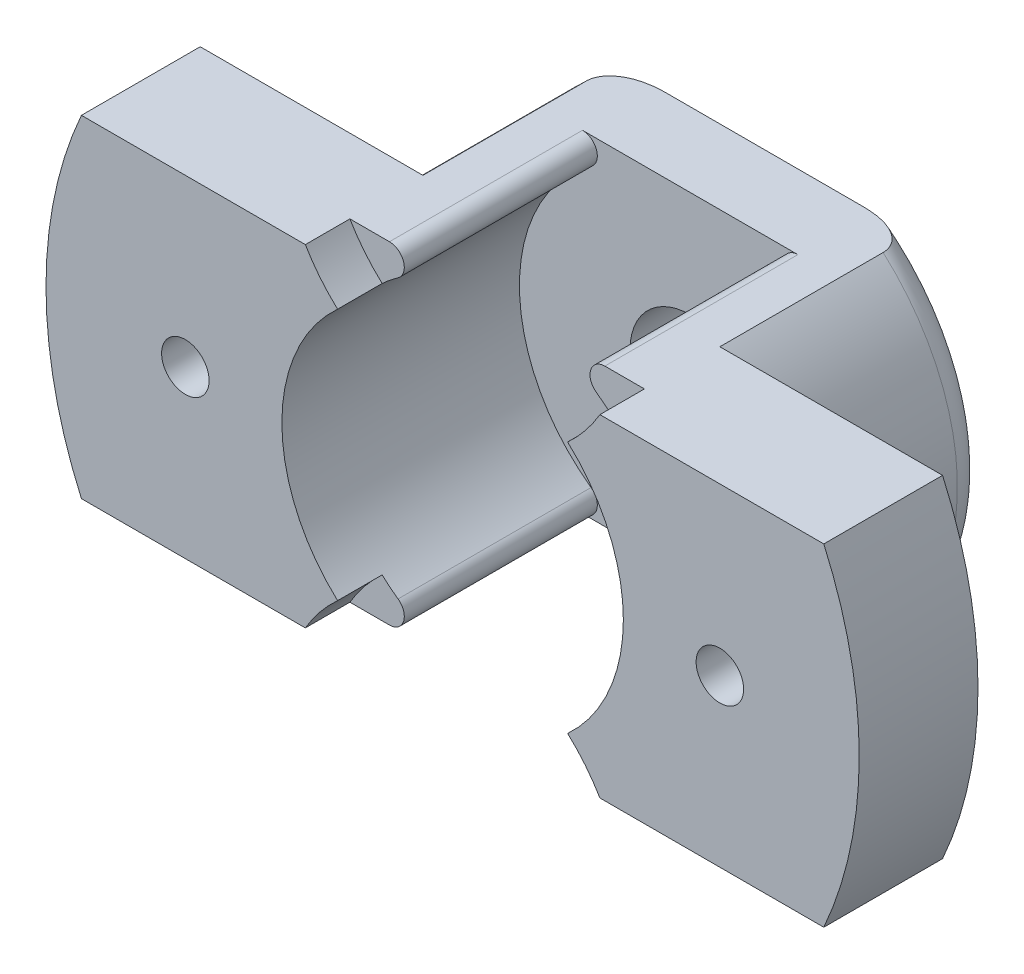
SolidWorks part; units mm, degrees
ref_plane "前视基准面" through (0, 0, 0) normal (0, 0, 1) x (1, 0, 0)
ref_plane "上视基准面" through (0, 0, 0) normal (0, 1, 0) x (1, 0, 0)
ref_plane "右视基准面" through (0, 0, 0) normal (1, 0, 0) x (0, 0, -1)
sketch "草图1" plane through (0, 0, 0) normal (0, 0, 1) x (1, 0, 0)
  line L0 (-10, 11.1803) -> (10, 11.1803)
  line L1 (-10, -11.1803) -> (10, -11.1803)
  line L2 (-10, 11.1803) -> (-10, -11.1803)
  line L3 (10, 11.1803) -> (10, -11.1803)
  circle A0 centre (0, 0) radius 15
  dimension "D1" = 30
  dimension "D2" = 20
extrude "凸台-拉伸1" add sketch "草图1" along normal blind 5 contours L2 A0 | L3 L0 L2 L1 | L3 A0
sketch "草图2" plane through (0, 0, 0) normal (0, 0, -1) x (-1, 0, 0)
  circle A0 centre (0, 0) radius 4.05
  dimension "D1" = 8.1
extrude "切除-拉伸1" cut sketch "草图2" against normal blind 5
sketch "草图3" plane through (0, 0, 5) normal (0, 0, 1) x (1, 0, 0)
  line L0 (-10, 11.1803) -> (10, 11.1803) construction
  line L1 (-10, 11.1803) -> (-2.6926, 11.1803)
  line L2 (-10, -11.1803) -> (10, -11.1803) construction
  line L3 (-10, -11.1803) -> (-2.6926, -11.1803)
  line L4 (2.6926, 11.1803) -> (10, 11.1803)
  line L5 (2.6926, -11.1803) -> (10, -11.1803)
  arc A1 (10, -11.1803) -> (10, 11.1803) centre (0, 0) ccw construction
  arc A2 (10, -11.1803) -> (10, 11.1803) centre (0, 0) ccw
  arc A3 (-10, 11.1803) -> (-10, -11.1803) centre (0, 0) ccw construction
  arc A4 (-10, 11.1803) -> (-10, -11.1803) centre (0, 0) ccw
  arc A6 (-2.6926, 11.1803) -> (-2.6926, -11.1803) centre (0, 0) ccw
  arc A7 (2.6926, -11.1803) -> (2.6926, 11.1803) centre (0, 0) ccw
  dimension "D1" = 23
extrude "凸台-拉伸2" add sketch "草图3" along normal blind 16
sketch "草图4" plane through (0, 0, 21) normal (0, 0, 1) x (1, 0, 0)
  line L0 (10, 11.1803) -> (2.6926, 11.1803) construction
  line L1 (10, -11.1803) -> (25, -11.1803)
  line L2 (2.6926, -11.1803) -> (10, -11.1803) construction
  line L3 (10, 11.1803) -> (25, 11.1803)
  line L4 (0, 0) -> (0, 11.1803) construction
  line L5 (-2.6926, 11.1803) -> (2.6926, 11.1803) construction
  arc A0 (-10, 11.1803) -> (-10, -11.1803) centre (0, 0) ccw construction
  arc A1 (10, -11.1803) -> (10, 11.1803) centre (0, 0) ccw construction
  arc A2 (-10, 11.1803) -> (-10, -11.1803) centre (0, 0) ccw
  arc A3 (10, -11.1803) -> (10, 11.1803) centre (0, 0) ccw
  arc A4 (25, -11.1803) -> (25, 11.1803) centre (0, 0) ccw
  dimension "D2" = 15
extrude "凸台-拉伸3" add sketch "草图4" against normal blind 8 contours L1 A4 L3 A3
mirror "镜向1" about plane through (0, 0, 0) normal (1, 0, 0) of "凸台-拉伸3"
sketch "草图5" plane through (0, 0, 21) normal (0, 0, 1) x (1, 0, 0)
  line L0 (0, -7.4334) -> (0, 8.8357) construction
  circle A0 centre (0, 17) radius 11.5
  circle A1 centre (0, -17) radius 11.5
  dimension "D1" = 23
  dimension "D3" = 23
  dimension "D2" = 17
  dimension "D4" = 17
extrude "切除-拉伸2" cut sketch "草图5" against normal blind 3
fillet "圆角2" radius 2 2 edges at (15, 0, 0) (-15, 0, 0)
sketch "草图6" plane through (0, 0, 21) normal (0, 0, 1) x (1, 0, 0)
  line L0 (0, 0) -> (28.574, 0) construction
  circle A0 centre (18, 0) radius 1.6
  circle A1 centre (-18, 0) radius 1.6
  dimension "D1" = 3.2
  dimension "D2" = 3.2
  dimension "D3" = 18
  dimension "D4" = 18
extrude "切除-拉伸3" cut sketch "草图6" against normal blind 13
fillet "圆角3" radius 1 4 edges at (2.6926, 11.1803, 11.5) (-2.6926, 11.1803, 11.5) (-2.6926, -11.1803, 11.5) (2.6926, -11.1803, 11.5)
